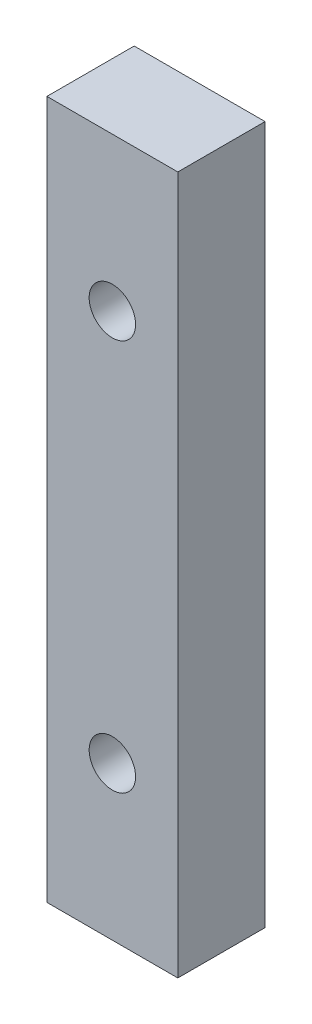
SolidWorks part; units mm, degrees
ref_plane "Front Plane" through (0, 0, 0) normal (0, 0, 1) x (1, 0, 0)
ref_plane "Top Plane" through (0, 0, 0) normal (0, 1, 0) x (1, 0, 0)
ref_plane "Right Plane" through (0, 0, 0) normal (1, 0, 0) x (0, 0, -1)
sketch "Sketch1" plane through (0, 0, 0) normal (0, 0, 1) x (1, 0, 0)
  line L0 (-9.525, 0) -> (9.525, 0) construction
  line L1 (-9.525, 50.8) -> (9.525, 50.8)
  line L2 (-9.525, 50.8) -> (-9.525, -50.8)
  line L3 (-9.525, -50.8) -> (9.525, -50.8)
  line L4 (9.525, 50.8) -> (9.525, -50.8)
  line L5 (0, -50.8) -> (0, 50.8) construction
  point P8 (0, 0)
  dimension "D1" = 19.05
  dimension "D2" = 101.6
extrude "Boss-Extrude1" add sketch "Sketch1" along normal blind 12.7
hole_wizard "1/4 Clearance Hole1" positions "Sketch2" profile "Sketch3" hole size "1/4" standard "ANSI Inch" end condition through all
sketch "Sketch2" plane through (0, 0, 12.7) normal (0, 0, 1) x (1, 0, 0)
  line L0 (0, -50.8) -> (0, 50.8) construction
  line L2 (-9.525, 0) -> (9.525, 0) construction
  line L4 (-9.525, 50.8) -> (-9.525, -50.8) construction
  line L5 (9.525, -50.8) -> (9.525, 50.8) construction
  point P0 (0, 28.5)
  point P2 (0, -28.5)
  dimension "D1" = 57
sketch "Sketch3" plane through (0, 28.5, 12.7) normal (1, 0, 0) x (0, -1, 0)
  line L0 (0, 0) -> (0, 12.7)
  line L1 (0, 12.7) -> (3.3782, 12.7)
  line L2 (3.3782, 12.7) -> (3.3782, 0)
  line L5 (3.3782, 0) -> (0, 0)
  line L11 (0, -6.35) -> (0, 107.95) construction
  dimension "Thru Hole Dia." = 6.7564
  dimension "Thru Hole Depth" = 12.7
